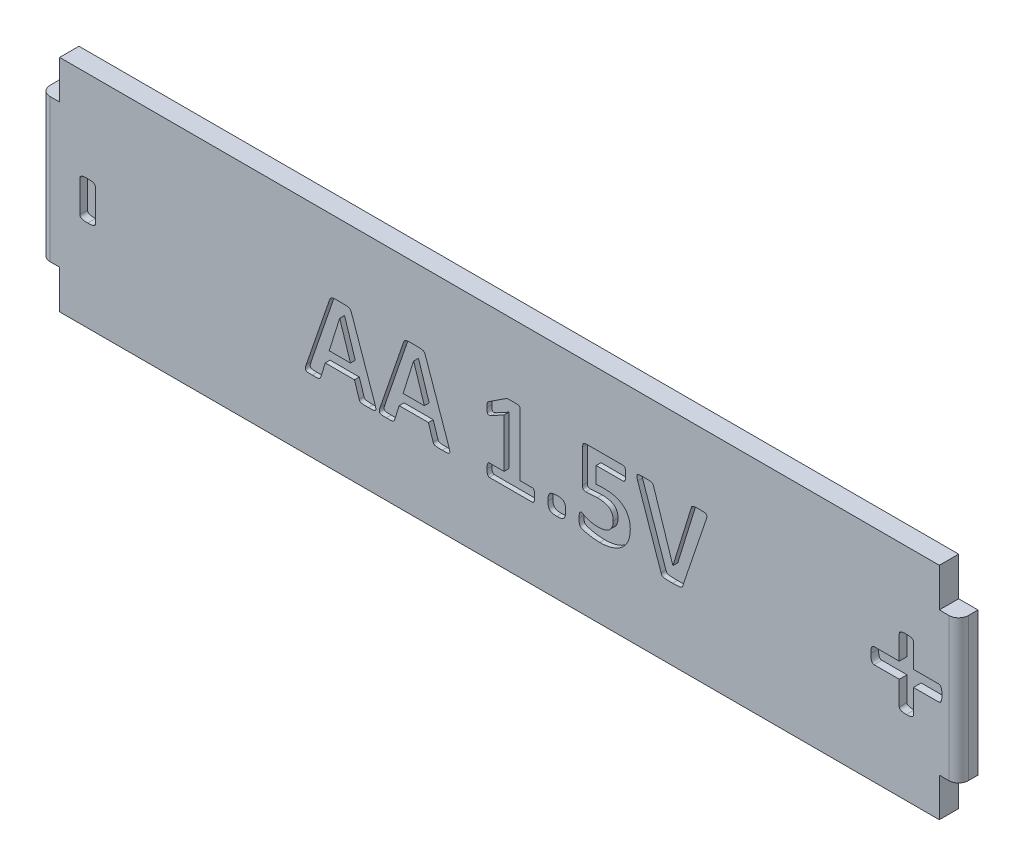
SolidWorks part; units mm, degrees
ref_plane "Front" through (0, 0, 0) normal (0, 0, 1) x (1, 0, 0)
ref_plane "Top" through (0, 0, 0) normal (0, 1, 0) x (1, 0, 0)
ref_plane "Right" through (0, 0, 0) normal (1, 0, 0) x (0, 0, -1)
sketch "Sketch1" plane through (0, 0, 0) normal (0, 0, 1) x (1, 0, 0)
  line L0 (-23.75, 0) -> (23.75, 0) construction
  line L1 (-22.75, -5.7) -> (22.75, -5.7)
  line L2 (-22.75, -5.7) -> (-22.75, -3.7)
  line L3 (-22.75, 5.7) -> (22.75, 5.7)
  line L4 (22.75, -5.7) -> (22.75, -3.7)
  line L5 (-22.75, -5.7) -> (22.75, 5.7) construction
  line L6 (-22.75, 5.7) -> (22.75, -5.7) construction
  line L17 (0, 5.7) -> (0, -5.7) construction
  line L18 (-23.75, 3.7) -> (-22.75, 3.7)
  line L19 (-23.75, 3.7) -> (-23.75, -3.7)
  line L20 (-23.75, -3.7) -> (-22.75, -3.7)
  line L22 (23.75, -3.7) -> (22.75, -3.7)
  line L23 (23.75, 3.7) -> (22.75, 3.7)
  line L24 (23.75, 3.7) -> (23.75, -3.7)
  line L25 (-22.75, 3.7) -> (-22.75, 5.7)
  line L26 (22.75, 3.7) -> (22.75, 5.7)
  point P0 (0, 0)
  point P14 (0, 0)
  dimension "D1" = 11.4
  dimension "D2" = 45.5
  dimension "D5" = 7.4
  dimension "D6" = 1
extrude "Boss-Extrude1" add sketch "Sketch1" along normal blind 1
fillet "Fillet1" radius 0.5 2 edges at (23.75, 0, 1) (-23.75, 0, 1)
sketch "Sketch2" plane through (0, 0, 1) normal (0, 0, 1) x (1, 0, 0)
  line L0 (-23.25, 0) -> (23.25, 0) construction
  line L1 (-23.25, 3.7) -> (-23.25, -3.7) construction
  line L2 (23.25, -3.7) -> (23.25, 3.7) construction
  line L3 (-23.25, -2) -> (23.25, -2) construction
  text T0 "<b>AA 1.5V</b>" font "Calibri" height 4
  dimension "D1" = 2
extrude "Cut-Extrude1" cut sketch "Sketch2" against normal blind 0.25
sketch "Sketch4" plane through (0, 0, 0) normal (0, 0, -1) x (-1, 0, 0)
  line L0 (-13.75, -1.05) -> (-13.75, 1.05) construction
  line L1 (-12.7, -1.05) -> (-14.8, -1.05)
  line L2 (-12.7, -1.05) -> (-12.7, 1.05)
  line L3 (-12.7, 1.05) -> (-14.8, 1.05)
  line L4 (-14.8, -1.05) -> (-14.8, 1.05)
  line L5 (-23.75, -3.7) -> (-23.75, 3.7) construction
  point P6 (-13.75, 0)
  point P9 (-23.75, 0)
  dimension "D1" = 10
  dimension "D2" = 2.1
  dimension "D3" = 2.1
extrude "Cut-Extrude3" cut sketch "Sketch4" against normal offset from surface (0.7 mm away) 0.3 up to face at (-4.3931, -0.6939, 1)
fillet "Fillet2" radius 0.4 4 edges at (12.7, -1.05, 0.35) (14.8, -1.05, 0.35) (12.7, 1.05, 0.35) (14.8, 1.05, 0.35)
sketch "Sketch6" plane through (0, 0, 1) normal (0, 0, 1) x (1, 0, 0)
  text T0 "<b>+</b>" font "Calibri" height 5
  text T1 "<b>-</b>" font "Calibri" height 5
extrude "Cut-Extrude4" cut sketch "Sketch6" against normal blind 0.4
